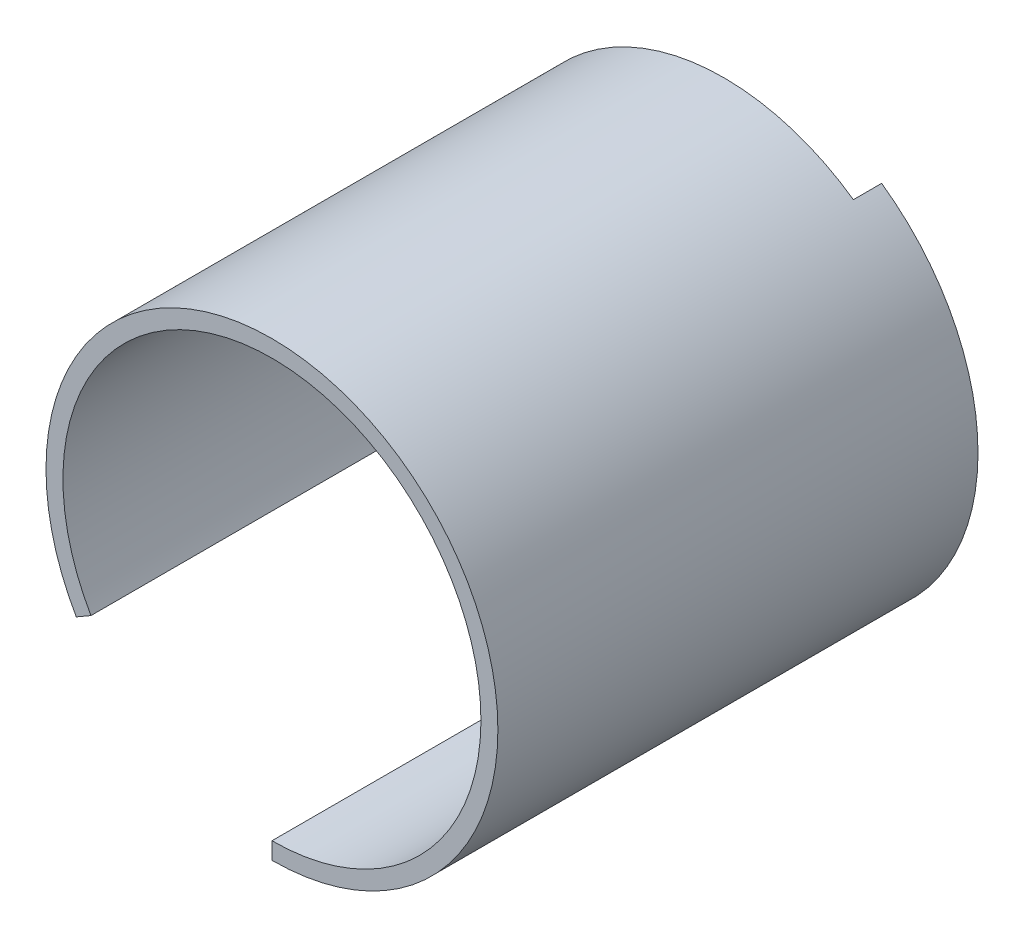
SolidWorks part; units mm, degrees
ref_plane "前基準面" through (0, 0, 0) normal (0, 0, 1) x (1, 0, 0)
ref_plane "上基準面" through (0, 0, 0) normal (0, 1, 0) x (1, 0, 0)
ref_plane "右基準面" through (0, 0, 0) normal (1, 0, 0) x (0, 0, -1)
sketch "草圖1" plane through (0, 0, 0) normal (0, 0, 1) x (1, 0, 0)
  line L0 (0, -37) -> (0, -40)
  line L1 (-34.641, -20) -> (-32.0429, -18.5)
  line L2 (0, 0) -> (0, -37) construction
  arc A0 (-32.0429, -18.5) -> (0, -37) centre (0, 0) cw
  arc A1 (-34.641, -20) -> (0, -40) centre (0, 0) cw
  point P6 (-32.0734, -18.4471)
  dimension "D2" = 40
  dimension "D1" = 3
  dimension "D3" = 60
extrude "填料-伸長1" add sketch "草圖1" along normal blind 80
sketch "草圖2" plane through (0, 0, 0) normal (0, 0, -1) x (-1, 0, 0)
  line L0 (0, -30) -> (0, -40)
  line L1 (-22.9431, 32.7661) -> (-17.2073, 24.5746)
  arc A0 (-22.9431, 32.7661) -> (0, -40) centre (0, 0) ccw
  arc A1 (34.641, -20) -> (0, -40) centre (0, 0) ccw construction
  arc A4 (-17.2073, 24.5746) -> (0, -30) centre (0, 0) ccw
  point P9 (-22.0484, 33.3747)
  point P10 (-17.559, 21.8417)
  dimension "D1" = 30
  dimension "D2" = 145
extrude "填料-伸長2" add sketch "草圖2" along normal blind 5
